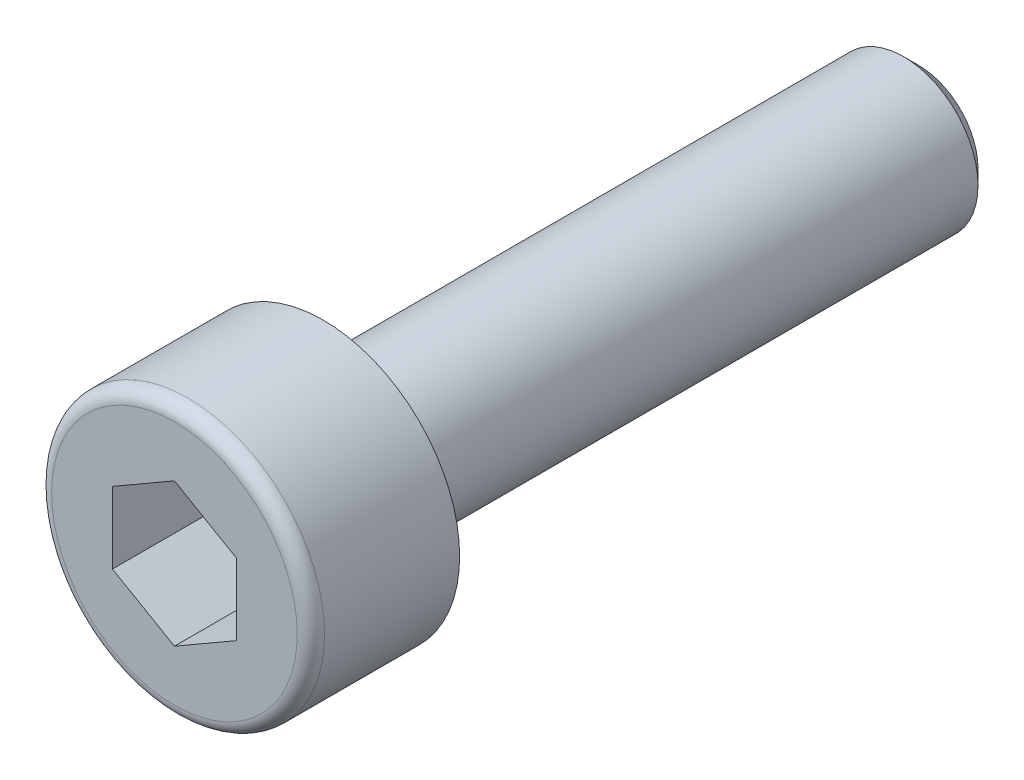
SolidWorks part; units mm, degrees
material "普通碳钢"
ref_plane "前视基准面" through (0, 0, 0) normal (0, 0, 1) x (1, 0, 0)
ref_plane "上视基准面" through (0, 0, 0) normal (0, 1, 0) x (1, 0, 0)
ref_plane "右视基准面" through (0, 0, 0) normal (1, 0, 0) x (0, 0, -1)
sketch "草图1" plane through (0, 0, 0) normal (1, 0, 0) x (0, 0, -1)
  line L0 (-3, 0) -> (30, 0) construction
  line L1 (-3, 0) -> (-3, 2.75)
  line L2 (-3, 2.75) -> (0, 2.75)
  line L3 (0, 2.75) -> (0, 1.5)
  line L4 (0, 1.5) -> (30, 1.5)
  line L5 (30, 1.5) -> (30, 0)
  point P3 (12, 1.5)
  dimension "A" = 5.5
  dimension "E" = 3
  dimension "L" = 30
  dimension "(e)" = 18
  dimension "M" = 3
sketch "草图2" plane through (0, 0, 0) normal (0, 0, 1) x (1, 0, 0)
  line L1 (0, 1.4434) -> (-1.25, 0.7217)
  line L2 (-1.25, 0.7217) -> (-1.25, -0.7217)
  line L3 (-1.25, -0.7217) -> (0, -1.4434)
  line L4 (0, -1.4434) -> (1.25, -0.7217)
  line L5 (1.25, -0.7217) -> (1.25, 0.7217)
  line L6 (1.25, 0.7217) -> (0, 1.4434)
  circle A0 centre (0, 0) radius 1.25 construction
  dimension "B" = 2.5
sketch "草图3" plane through (0, 0, 0) normal (1, 0, 0) x (0, 0, -1)
  line L0 (-3, 0) -> (-3, 2.75) construction
  line L1 (-3, 2.75) -> (0, 2.75) construction
  line L3 (0, 2.75) -> (0, 1.5) construction
  line L6 (-3, 0) -> (-3, 2.75)
  line L7 (-3, 2.75) -> (0, 2.75)
  line L8 (0, 1.5) -> (12, 1.5)
  line L9 (0, 2.75) -> (0, 1.5)
  line L10 (-3, 0) -> (12, 0)
  line L11 (12, 1.5) -> (12, 0)
  dimension "D1" = 12
revolve "旋转1" add sketch "草图3" angle 360 about L10
cosmetic thread "装饰螺纹线1" parameters "D2"=2.459
sketch "草图4" plane through (0, 0, 3) normal (0, 0, 1) x (1, 0, 0)
  line L0 (0, 1.4434) -> (-1.25, 0.7217) construction
  line L1 (-1.25, 0.7217) -> (-1.25, -0.7217) construction
  line L2 (-1.25, -0.7217) -> (0, -1.4434) construction
  line L3 (0, -1.4434) -> (1.25, -0.7217) construction
  line L4 (1.25, -0.7217) -> (1.25, 0.7217) construction
  line L5 (1.25, 0.7217) -> (0, 1.4434) construction
  line L6 (0, 1.4434) -> (-1.25, 0.7217)
  line L7 (-1.25, 0.7217) -> (-1.25, -0.7217)
  line L8 (-1.25, -0.7217) -> (0, -1.4434)
  line L9 (0, -1.4434) -> (1.25, -0.7217)
  line L10 (1.25, -0.7217) -> (1.25, 0.7217)
  line L11 (1.25, 0.7217) -> (0, 1.4434)
extrude "切除-拉伸1" cut sketch "草图4" against normal blind 1.925
fillet "圆角1" radius 0.275 1 edges at (2.75, 0, 3)
chamfer "倒角1" distance 0.3 angle 45 1 edges at (1.5, 0, -12)
